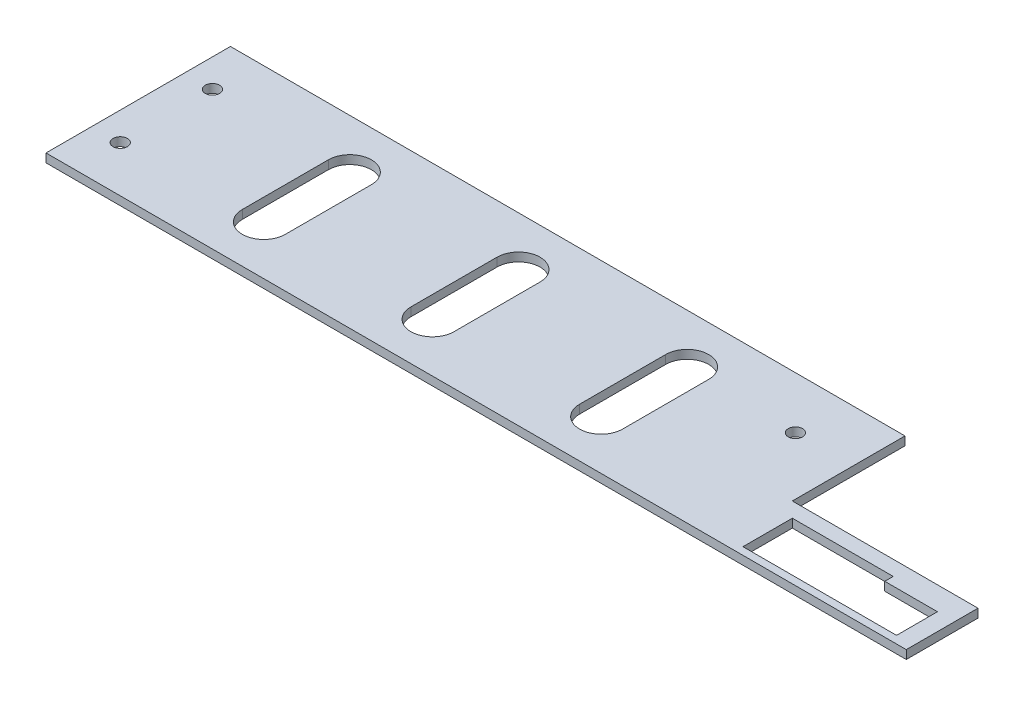
SolidWorks part; units mm, degrees
material "Custom Plastic"
ref_plane "Plan de face" through (0, 0, 0) normal (0, 0, 1) x (1, 0, 0)
ref_plane "Plan de dessus" through (0, 0, 0) normal (0, 1, 0) x (1, 0, 0)
ref_plane "Plan de droite" through (0, 0, 0) normal (1, 0, 0) x (0, 0, -1)
sketch "Esquisse1" plane through (0, 0, 0) normal (0, 1, 0) x (1, 0, 0)
  line L1 (-161.1743, 28.77) -> (138.6257, 28.77) construction
  line L2 (-161.1743, 28.77) -> (-161.1743, -35.5) construction
  line L3 (-161.1743, -35.5) -> (138.6257, -35.5) construction
  line L4 (138.6257, 28.77) -> (138.6257, -35.5) construction
  line L5 (-161.1743, 28.77) -> (138.6257, -35.5) construction
  line L6 (-161.1743, -35.5) -> (138.6257, 28.77) construction
  line L7 (138.6257, 18.77) -> (138.6257, -25.5) construction
  line L9 (-161.1743, 18.77) -> (-161.1743, -25.5)
  line L10 (-161.1743, 18.77) -> (-151.1743, 18.77) construction
  line L12 (-161.1743, -35.5) -> (138.6257, -35.5)
  line L13 (114.2615, -15.6877) -> (114.2615, -18.6342)
  line L14 (-151.1743, 28.77) -> (-151.1743, 18.77) construction
  line L15 (73.912, -0.4751) -> (73.912, -50000.4751) construction
  line L16 (-161.1743, -25.5) -> (-151.1743, -25.5) construction
  line L17 (-151.1743, -25.5) -> (-151.1743, -35.5) construction
  line L18 (67.162, 10.635) -> (53.862, 10.635) construction
  line L19 (-161.1743, 18.77) -> (138.6257, 18.77) construction
  line L20 (73.912, 28.77) -> (73.912, -10.5)
  line L21 (138.6257, -25.5) -> (-161.1743, -25.5) construction
  line L26 (114.2615, -15.6877) -> (79.1092, -15.6877)
  line L28 (-161.3743, 28.77) -> (-161.3743, -35.5) construction
  line L29 (114.2615, -15.6877) -> (114.2615, -32.887) construction
  line L30 (-161.1743, -25.5) -> (-161.1743, -35.5)
  line L33 (-161.1743, 28.77) -> (-161.1743, 18.77)
  line L34 (-161.1743, 28.77) -> (73.912, 28.77)
  line L36 (73.912, -10.5) -> (138.6257, -10.5)
  line L37 (138.6257, -10.5) -> (138.6257, -35.5)
  line L38 (114.2615, -32.887) -> (79.1092, -32.887)
  line L39 (138.6257, -35.5) -> (-161.3743, -35.5) construction
  line L40 (79.1092, -15.6877) -> (79.1092, -32.887)
  line L41 (114.2615, -15.6877) -> (79.1092, -32.887) construction
  line L42 (114.2615, -32.887) -> (79.1092, -15.6877) construction
  line L43 (-161.1743, -35.5) -> (-161.3743, -35.5) construction
  line L44 (132.6257, -18.6342) -> (114.2615, -18.6342)
  line L45 (132.6257, -18.6342) -> (132.6257, -32.887)
  line L46 (132.6257, -32.887) -> (114.2615, -32.887)
  line L47 (138.6257, -10.5) -> (73.912, -10.5) construction
  line L48 (114.2615, -18.6342) -> (114.2615, -32.887) construction
  line L49 (132.6257, -18.6342) -> (114.2615, -32.887) construction
  line L50 (73.912, 28.77) -> (73.912, -7.5) construction
  line L51 (132.6257, -32.887) -> (114.2615, -18.6342) construction
  circle A17 centre (-151.3743, -19.4325) radius 2.5
  circle A18 centre (-151.3743, 12.7025) radius 2.5
  circle A19 centre (67.162, 10.635) radius 2.5 construction
  circle A20 centre (-151.3743, 12.7025) radius 2.5 construction
  circle A21 centre (-151.3743, -19.4325) radius 2.5 construction
  circle A22 centre (53.862, 10.635) radius 2.5
  circle A28 centre (67.162, 10.635) radius 2.5 construction
  point P4 (-11.2743, -3.365)
  point P45 (123.4436, -25.7606)
  point P56 (96.6853, -24.2874)
  dimension "D3" = 10
  dimension "D4" = 35.1524
  dimension "D5" = 6
  dimension "D7" = 5
  dimension "D2" = 18.3642
  dimension "D1" = 0.2
  dimension "D6" = 13.3
extrude "Boss.-Extru.1" add sketch "Esquisse1" along normal blind 3
sketch "Esquisse2" plane through (0, 0, 0) normal (0, -1, 0) x (1, 0, 0)
  line L0 (73.912, -28.77) -> (73.912, -38.77) construction
  line L1 (73.912, -38.77) -> (-43.6312, -38.77) construction
  line L2 (-43.6312, -38.77) -> (-161.1743, -38.77) construction
  line L3 (-161.1743, -38.77) -> (-161.1743, -28.77) construction
  line L4 (-155.8759, 3.365) -> (-167.4129, 3.365) construction
  line L5 (-161.1743, -28.77) -> (-161.1743, 35.5) construction
  line L6 (15.1404, -38.77) -> (15.1404, -50038.77) construction
  line L7 (-43.6312, -38.77) -> (-43.6312, -50038.77) construction
  line L8 (-102.4027, -38.77) -> (-102.4027, -50038.77) construction
  line L9 (7.6404, -11.635) -> (7.6404, 18.365)
  line L10 (22.6404, 18.365) -> (22.6404, -11.635)
  line L11 (22.6404, -11.635) -> (7.6404, -11.635) construction
  line L12 (7.6404, 18.365) -> (22.6404, 18.365) construction
  line L13 (22.6404, 3.365) -> (7.6404, 3.365) construction
  line L14 (-51.1312, -11.635) -> (-51.1312, 18.365)
  line L15 (-36.1312, 18.365) -> (-36.1312, -11.635)
  line L16 (-36.1312, -11.635) -> (-51.1312, -11.635) construction
  line L17 (-51.1312, 18.365) -> (-36.1312, 18.365) construction
  line L18 (-36.1312, 3.365) -> (-51.1312, 3.365) construction
  line L19 (-109.9027, -11.635) -> (-109.9027, 18.365)
  line L20 (-94.9027, 18.365) -> (-94.9027, -11.635)
  line L21 (-94.9027, -11.635) -> (-109.9027, -11.635) construction
  line L22 (-109.9027, 18.365) -> (-94.9027, 18.365) construction
  line L23 (-94.9027, 3.365) -> (-109.9027, 3.365) construction
  arc A0 (7.6404, -11.635) -> (22.6404, -11.635) centre (15.1404, -11.635) ccw
  arc A1 (7.6404, 18.365) -> (22.6404, 18.365) centre (15.1404, 18.365) cw
  arc A2 (-51.1312, -11.635) -> (-36.1312, -11.635) centre (-43.6312, -11.635) ccw
  arc A3 (-51.1312, 18.365) -> (-36.1312, 18.365) centre (-43.6312, 18.365) cw
  arc A4 (-109.9027, -11.635) -> (-94.9027, -11.635) centre (-102.4027, -11.635) ccw
  arc A5 (-109.9027, 18.365) -> (-94.9027, 18.365) centre (-102.4027, 18.365) cw
  point P8 (-161.1743, 3.365)
  point P10 (15.1404, -38.77)
  point P13 (-102.4027, -38.77)
  point P30 (15.1404, 3.365)
  point P41 (-43.6312, 3.365)
  point P51 (-102.4027, 3.365)
  dimension "D1" = 10
  dimension "D6" = 15
  dimension "D7" = 30
extrude "Enlèv. mat.-Extru.1" cut sketch "Esquisse2" against normal through all
